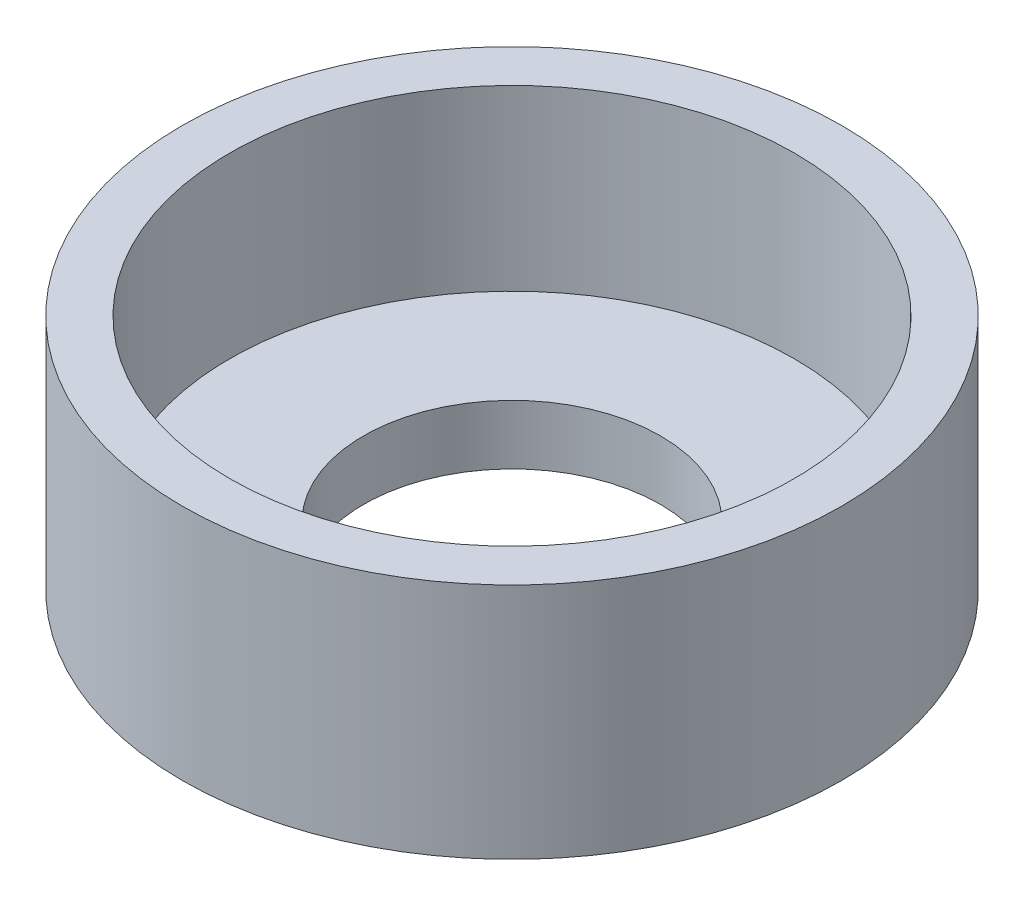
SolidWorks part; units mm, degrees
ref_plane "Front Plane" through (0, 0, 0) normal (0, 0, 1) x (1, 0, 0)
ref_plane "Top Plane" through (0, 0, 0) normal (0, 1, 0) x (1, 0, 0)
ref_plane "Right Plane" through (0, 0, 0) normal (1, 0, 0) x (0, 0, -1)
sketch "Sketch1" plane through (0, 0, 0) normal (0, 1, 0) x (1, 0, 0)
  circle A2 centre (0, 0) radius 5
  circle A3 centre (0, 0) radius 11.1
  dimension "D1" = 22.2
  dimension "D2" = 10
extrude "Boss-Extrude1" add sketch "Sketch1" along normal blind 2
sketch "Sketch2" plane through (0, 2, 0) normal (0, 1, 0) x (1, 0, 0)
  circle A0 centre (0, 0) radius 9.5
  circle A1 centre (0, 0) radius 11.1
  dimension "D1" = 19
  dimension "D2" = 22.2
extrude "Boss-Extrude2" add sketch "Sketch2" along normal blind 6
